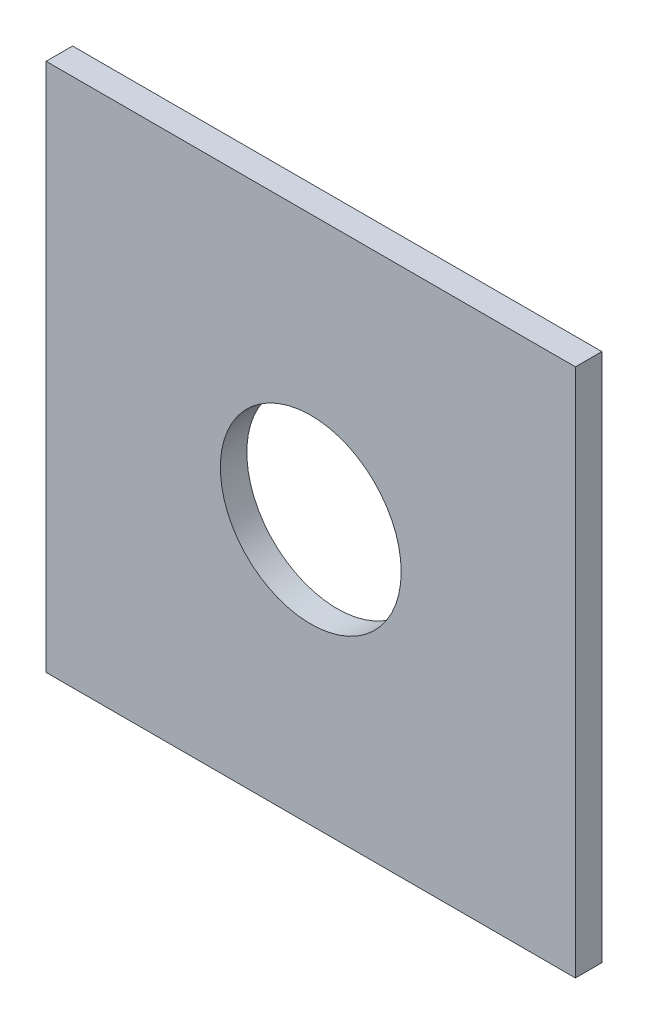
SolidWorks part; units mm, degrees
ref_plane "Front Plane" through (0, 0, 0) normal (0, 0, 1) x (1, 0, 0)
ref_plane "Top Plane" through (0, 0, 0) normal (0, 1, 0) x (1, 0, 0)
ref_plane "Right Plane" through (0, 0, 0) normal (1, 0, 0) x (0, 0, -1)
sketch "Sketch1" plane through (0, 0, 0) normal (0, 0, 1) x (1, 0, 0)
  line L1 (-30, -30) -> (30, -30)
  line L2 (-30, -30) -> (-30, 30)
  line L3 (-30, 30) -> (30, 30)
  line L4 (30, -30) -> (30, 30)
  line L5 (-30, -30) -> (30, 30) construction
  line L6 (-30, 30) -> (30, -30) construction
  point P0 (0, 0)
  dimension "D1" = 60
  dimension "D2" = 60
extrude "Boss-Extrude1" add sketch "Sketch1" along normal blind 3
sketch "Sketch2" plane through (0, 0, 3) normal (0, 0, 1) x (1, 0, 0)
  circle A0 centre (0, 0) radius 10.25
extrude "Cut-Extrude1" cut sketch "Sketch2" against normal through all
